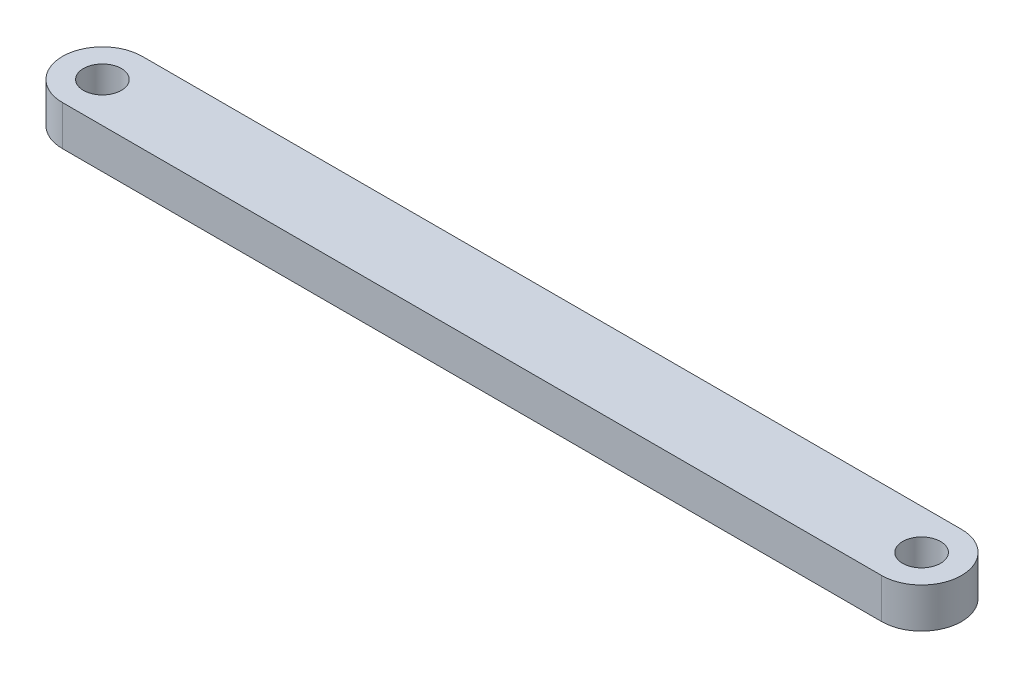
SolidWorks part; units mm, degrees
ref_plane "Front Plane" through (0, 0, 0) normal (0, 0, 1) x (1, 0, 0)
ref_plane "Top Plane" through (0, 0, 0) normal (0, 1, 0) x (1, 0, 0)
ref_plane "Right Plane" through (0, 0, 0) normal (1, 0, 0) x (0, 0, -1)
sketch "Sketch2" plane through (0, 0, 0) normal (0, 1, 0) x (1, 0, 0)
  line L0 (20.5, 0) -> (-20.5, 0) construction
  line L1 (20.5, -2) -> (-20.5, -2)
  line L2 (20.5, 2) -> (-20.5, 2)
  arc A0 (20.5, -2) -> (20.5, 2) centre (20.5, 0) ccw
  arc A1 (-20.5, 2) -> (-20.5, -2) centre (-20.5, 0) ccw
  circle A2 centre (-20.5, 0) radius 0.95
  circle A3 centre (20.5, 0) radius 0.95
  point P2 (0, 0)
  dimension "D2" = 2
  dimension "D3" = 1.9
  dimension "D4" = 1.9
  dimension "D1" = 41
extrude "Boss-Extrude1" add sketch "Sketch2" along normal mid plane 2
